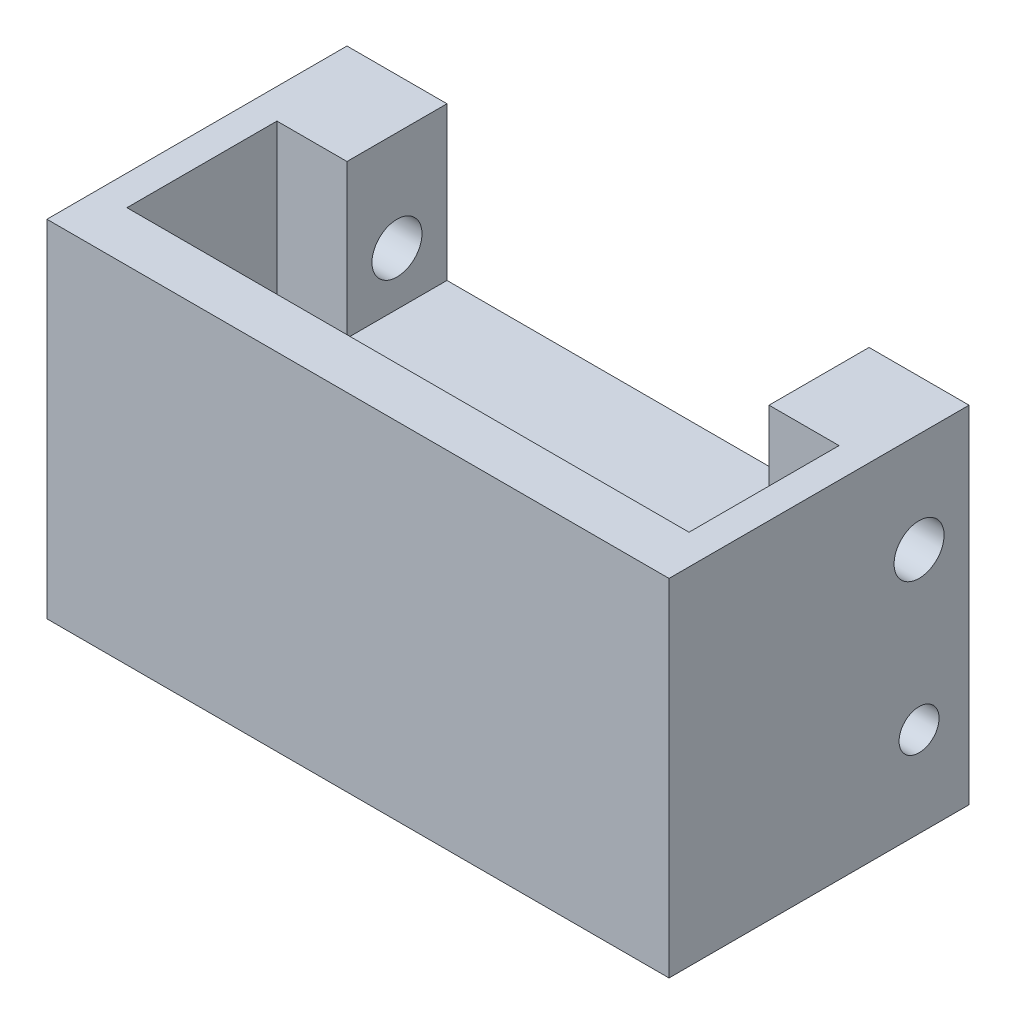
SolidWorks part; units mm, degrees
material "Thornel VCB-20 Carbon Cloth"
ref_plane "Front Plane" through (0, 0, 0) normal (0, 0, 1) x (1, 0, 0)
ref_plane "Top Plane" through (0, 0, 0) normal (0, 1, 0) x (1, 0, 0)
ref_plane "Right Plane" through (0, 0, 0) normal (1, 0, 0) x (0, 0, -1)
sketch "Sketch1" plane through (0, 0, 0) normal (0, 0, 1) x (1, 0, 0)
  line L1 (-19.5853, 31.9893) -> (-6.8853, 31.9893)
  line L2 (-19.5853, 31.9893) -> (-19.5853, -11.9527)
  line L3 (-19.5853, -11.9527) -> (-6.8853, -11.9527)
  line L4 (-6.8853, 31.9893) -> (-6.8853, -11.9527)
  line L5 (46.7087, 31.9893) -> (59.4087, 31.9893)
  line L6 (46.7087, 31.9893) -> (46.7087, -11.9527)
  line L7 (46.7087, -11.9527) -> (59.4087, -11.9527)
  line L8 (59.4087, 31.9893) -> (59.4087, -11.9527)
  dimension "D1" = 12.7
  dimension "D2" = 43.942
  dimension "D3" = 12.7
  dimension "D4" = 43.942
  dimension "D5" = 53.594
extrude "Boss-Extrude1" add sketch "Sketch1" along normal blind 12.7
sketch "Sketch2" plane through (-19.5853, 0, 0) normal (-1, 0, 0) x (0, 0, 1)
  circle A0 centre (6.35, 19.2893) radius 3.175
  circle A1 centre (6.35, -0.5227) radius 2.54
  dimension "D3" = 6.35
  dimension "D5" = 5.08
  dimension "D1" = 12.7
  dimension "D2" = 6.35
  dimension "D4" = 19.812
  dimension "D6" = 6.35
extrude "Cut-Extrude1" cut sketch "Sketch2" against normal through all
sketch "Sketch4" plane through (-6.8853, 0, 0) normal (1, 0, 0) x (0, 0, -1)
  line L0 (-12.7, -11.9527) -> (-12.7, 31.9893) construction
  line L1 (-12.7, 12.5583) -> (0, 12.5583)
  line L2 (-12.7, 12.5583) -> (-12.7, 7.4783)
  line L3 (-12.7, 7.4783) -> (0, 7.4783)
  line L4 (0, 12.5583) -> (0, 7.4783)
  line L5 (0, -11.9527) -> (0, 31.9893) construction
  point P10 (0, 0)
  dimension "D3" = 19.431
  dimension "D1" = 12.7
  dimension "D2" = 5.08
extrude "Boss-Extrude3" add sketch "Sketch4" along normal up to next
sketch "Sketch5" plane through (0, 0, 12.7) normal (0, 0, 1) x (1, 0, 0)
  line L0 (-19.5853, -11.9527) -> (-6.8853, -11.9527) construction
  line L1 (-19.5853, 31.9893) -> (-15.7753, 31.9893)
  line L2 (-19.5853, 31.9893) -> (-19.5853, -11.9527)
  line L3 (-19.5853, -11.9527) -> (-15.7753, -11.9527)
  line L4 (-15.7753, 31.9893) -> (-15.7753, -11.9527)
  line L5 (46.7087, -11.9527) -> (59.4087, -11.9527) construction
  line L6 (59.4087, 31.9893) -> (55.5987, 31.9893)
  line L7 (59.4087, 31.9893) -> (59.4087, -11.9527)
  line L8 (59.4087, -11.9527) -> (55.5987, -11.9527)
  line L9 (55.5987, 31.9893) -> (55.5987, -11.9527)
  dimension "D1" = 3.81
  dimension "D2" = 3.81
extrude "Boss-Extrude4" add sketch "Sketch5" along normal blind 19.05
sketch "Sketch6" plane through (0, 0, 31.75) normal (0, 0, 1) x (1, 0, 0)
  line L1 (-19.5853, 31.9893) -> (59.4087, 31.9893)
  line L2 (-19.5853, 31.9893) -> (-19.5853, -11.9527)
  line L3 (-19.5853, -11.9527) -> (59.4087, -11.9527)
  line L4 (59.4087, 31.9893) -> (59.4087, -11.9527)
extrude "Boss-Extrude5" add sketch "Sketch6" along normal blind 6.35
